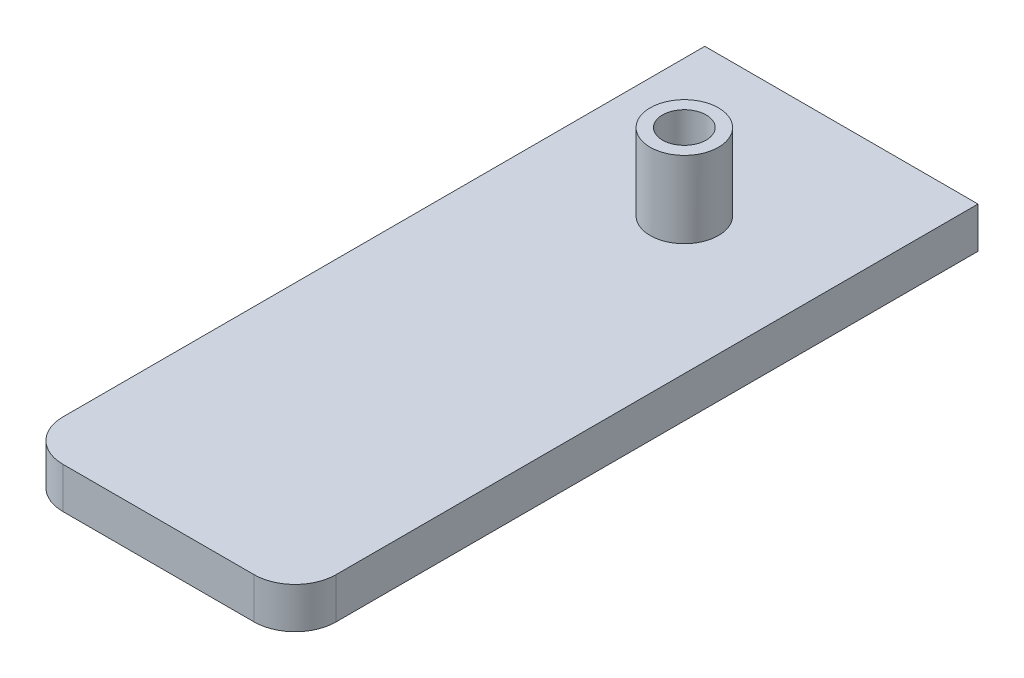
SolidWorks part; units mm, degrees
ref_plane "Front Plane" through (0, 0, 0) normal (0, 0, 1) x (1, 0, 0)
ref_plane "Top Plane" through (0, 0, 0) normal (0, 1, 0) x (1, 0, 0)
ref_plane "Right Plane" through (0, 0, 0) normal (1, 0, 0) x (0, 0, -1)
sketch "Sketch1" plane through (0, 0, 0) normal (0, 1, 0) x (1, 0, 0)
  line L1 (-10, -25) -> (10, -25)
  line L2 (-10, -25) -> (-10, 25)
  line L3 (-10, 25) -> (10, 25)
  line L4 (10, -25) -> (10, 25)
  line L5 (-10, -25) -> (10, 25) construction
  line L6 (-10, 25) -> (10, -25) construction
  point P0 (0, 0)
extrude "Boss-Extrude1" add sketch "Sketch1" along normal blind 3
sketch "Sketch3" plane through (0, 0, 0) normal (0, -1, 0) x (1, 0, 0)
  circle A0 centre (0, -13.5) radius 1.6
extrude "Cut-Extrude1" cut sketch "Sketch3" against normal blind 10
sketch "Sketch4" plane through (0, 3, 0) normal (0, 1, 0) x (1, 0, 0)
  circle A0 centre (0, 13.5) radius 2.5
  circle A1 centre (0, 13.5) radius 1.6
extrude "Boss-Extrude4" add sketch "Sketch4" along normal blind 5.6
fillet "Fillet1" radius 3 2 edges at (-10, 1.5, 25) (10, 1.5, 25)
